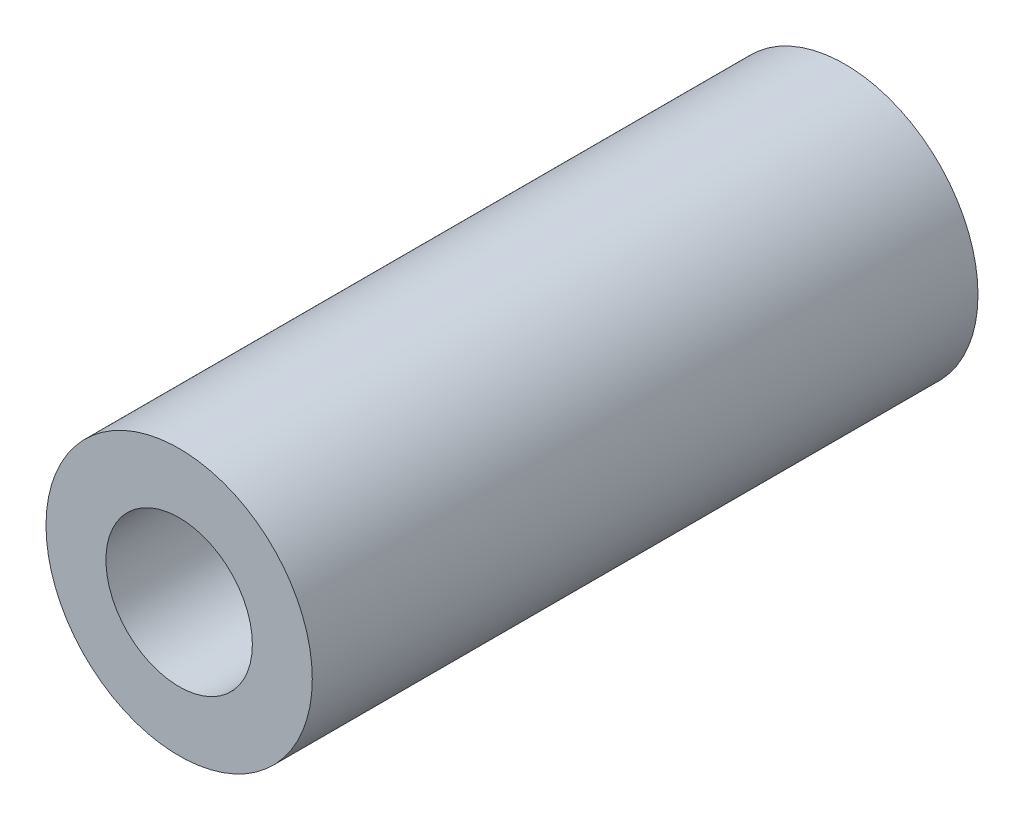
SolidWorks part; units mm, degrees
ref_plane "前视基准面" through (0, 0, 0) normal (0, 0, 1) x (1, 0, 0)
ref_plane "上视基准面" through (0, 0, 0) normal (0, 1, 0) x (1, 0, 0)
ref_plane "右视基准面" through (0, 0, 0) normal (1, 0, 0) x (0, 0, -1)
other "Configuration Table"
sketch "草图1" plane through (0, 0, 0) normal (0, 0, 1) x (1, 0, 0)
  circle A0 centre (0, 0) radius 2
  circle A1 centre (0, 0) radius 1.1
extrude "10mm铝柱_M2简化内孔" add sketch "草图1" along normal blind 10
